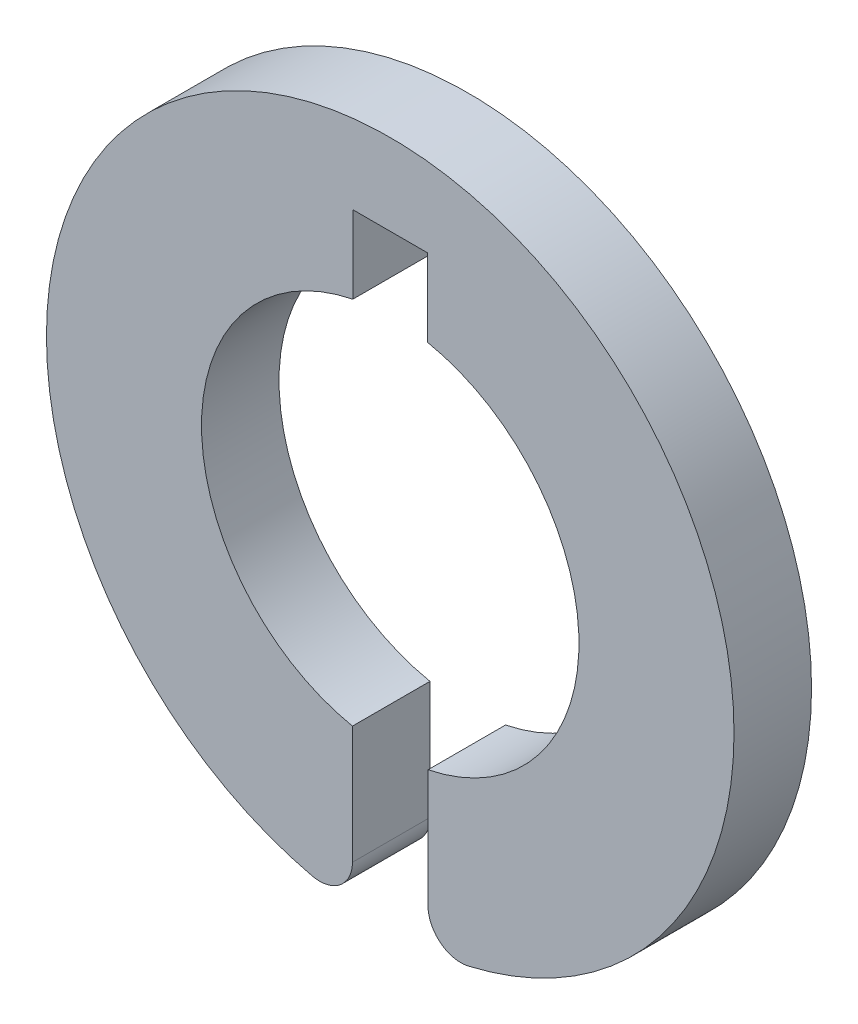
SolidWorks part; units mm, degrees
material "Acrylic (Medium-high impact)"
ref_plane "Front Plane" through (0, 0, 0) normal (0, 0, 1) x (1, 0, 0)
ref_plane "Top Plane" through (0, 0, 0) normal (0, 1, 0) x (1, 0, 0)
ref_plane "Right Plane" through (0, 0, 0) normal (1, 0, 0) x (0, 0, -1)
sketch "스케치1" plane through (0, 0, 0) normal (0, 0, 1) x (1, 0, 0)
  line L0 (0, 10.85) -> (0, 0) construction
  line L6 (-1.4475, 10.1576) -> (1.4475, 10.1576)
  line L7 (0, 0) -> (0, -10.1882) construction
  line L8 (-1.4625, -13.2219) -> (1.4625, -13.2219) construction
  line L9 (-1.4625, -13.2219) -> (-1.4625, -7.1546)
  line L10 (-1.4625, -7.1546) -> (1.4625, -7.1546) construction
  line L11 (1.4625, -13.2219) -> (1.4625, -7.1546)
  line L12 (-1.4625, -13.2219) -> (1.4625, -7.1546) construction
  line L13 (-1.4625, -7.1546) -> (1.4625, -13.2219) construction
  line L14 (-1.4475, 10.1576) -> (-1.4475, 7.1576)
  line L15 (-1.4475, 7.1576) -> (1.4475, 7.1576) construction
  line L16 (1.4475, 10.1576) -> (1.4475, 7.1576)
  line L17 (-1.4475, 10.1576) -> (1.4475, 7.1576) construction
  line L18 (-1.4475, 7.1576) -> (1.4475, 10.1576) construction
  circle A0 centre (0, 0) radius 13.3025 construction
  circle A1 centre (0, 0) radius 7.3025 construction
  arc A2 (-1.4625, -13.2219) -> (1.4625, -13.2219) centre (0, 0) cw
  arc A3 (1.4625, -7.1546) -> (1.4475, 7.1576) centre (0, 0) ccw
  arc A4 (-1.4475, 7.1576) -> (-1.4625, -7.1546) centre (0, 0) ccw
  point P2 (0, 10.85)
  point P5 (0, 8.6576)
  point P10 (0, -10.1882)
  dimension "D1" = 6
  dimension "D2" = 14.605
  dimension "D3" = 2.895
  dimension "D4" = 3
  dimension "D5" = 2.925
extrude "보스-돌출1" add sketch "스케치1" along normal blind 3
fillet "필렛1" radius 1.27 2 edges at (-1.4625, -13.2219, 1.5) (1.4625, -13.2219, 1.5)
